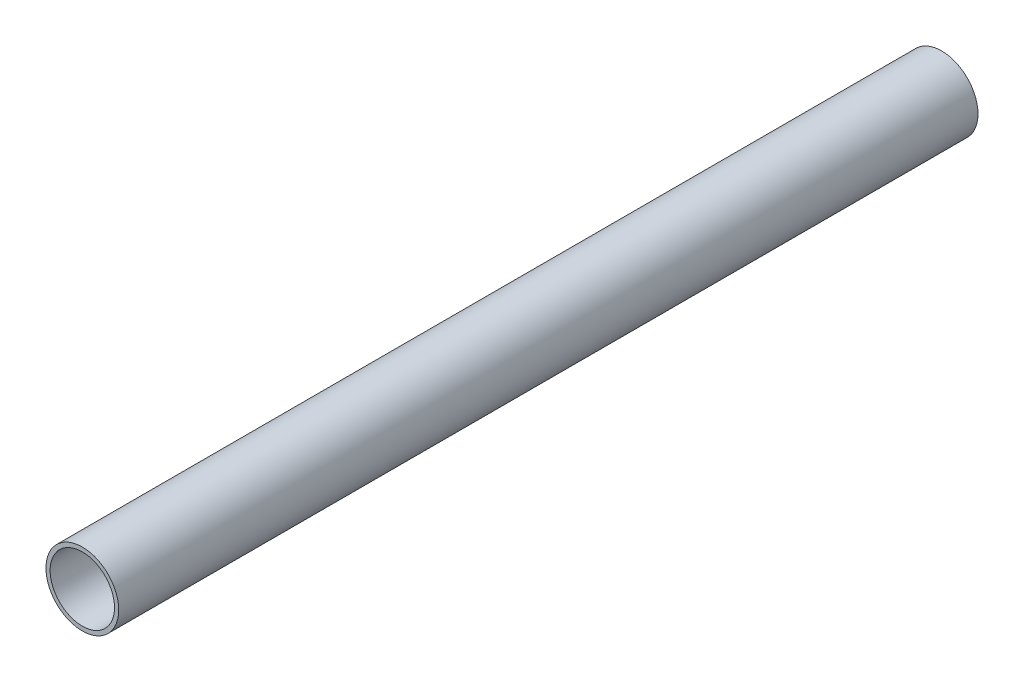
SolidWorks part; units mm, degrees
ref_plane "front" through (0, 0, 0) normal (0, 0, 1) x (1, 0, 0)
ref_plane "top" through (0, 0, 0) normal (0, 1, 0) x (1, 0, 0)
ref_plane "right" through (0, 0, 0) normal (1, 0, 0) x (0, 0, -1)
sketch "Sketch1" plane through (0, 0, 0) normal (0, 0, 1) x (1, 0, 0)
  circle A0 centre (0, 0) radius 25.273
  circle A1 centre (0, 0) radius 22.352
  dimension "D1" = 50.546
  dimension "D2" = 2.921
extrude "Base-Extrude" add sketch "Sketch1" against normal blind 596.9
